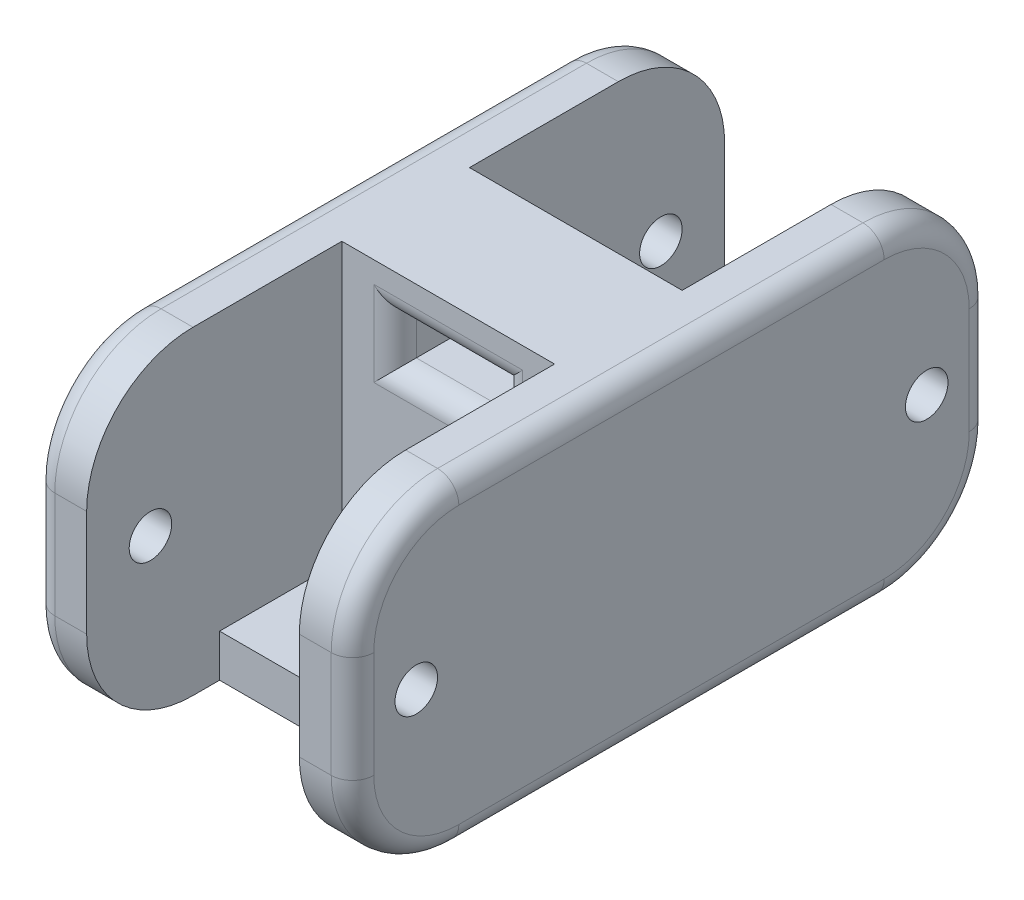
SolidWorks part; units mm, degrees
ref_plane "Front Plane" through (0, 0, 0) normal (0, 0, 1) x (1, 0, 0)
ref_plane "Top Plane" through (0, 0, 0) normal (0, 1, 0) x (1, 0, 0)
ref_plane "Right Plane" through (0, 0, 0) normal (1, 0, 0) x (0, 0, -1)
sketch "Bottom Section Base Sketch" plane through (0, 0, 0) normal (0, 0, 1) x (1, 0, 0)
  line L1 (-7.5, 7.5) -> (7.5, 7.5)
  line L2 (-7.5, 7.5) -> (-7.5, -7.5)
  line L3 (-7.5, -7.5) -> (7.5, -7.5)
  line L4 (7.5, 7.5) -> (7.5, -7.5)
  line L5 (-7.5, 7.5) -> (7.5, -7.5) construction
  line L6 (-7.5, -7.5) -> (7.5, 7.5) construction
  point P0 (0, 0)
  dimension "D1" = 15
  dimension "D2" = 15
extrude "Bottom Section Extrude" add sketch "Bottom Section Base Sketch" along normal blind 30
sketch "Hinge Cutout Sketch" plane through (0, 0, 0) normal (0, 0, 1) x (1, 0, 0)
  line L1 (5, 7.5) -> (-5, 7.5)
  line L2 (5, 7.5) -> (5, -7.5)
  line L3 (5, -7.5) -> (-5, -7.5)
  line L4 (-5, 7.5) -> (-5, -7.5)
  line L5 (7.5, -7.5) -> (7.5, 7.5) construction
  line L6 (0, 0) -> (0, 10.7526) construction
  line L7 (7.5, 7.5) -> (-7.5, 7.5) construction
  line L8 (0, 0) -> (-12.6441, 0) construction
  dimension "D1" = 2.5
extrude "Hinge Cutout Extruded Cut" cut sketch "Hinge Cutout Sketch" along normal blind 12
sketch "Hinge Hole Sketch" plane through (7.5, 0, 0) normal (1, 0, 0) x (0, 0, -1)
  line L0 (0, 0) -> (-29.5332, 0) construction
  line L1 (0, -7.5) -> (0, 7.5) construction
  circle A0 centre (-3, 0) radius 1
  dimension "D1" = 2
  dimension "D2" = 3
extrude "Hinge Hole Extruded Cut" cut sketch "Hinge Hole Sketch" against normal through all
ref_plane "Part Midplane Relative to Front Plane" through (0, 0, 15) normal (0, 0, 1) x (1, 0, 0)
mirror "Hinge and Hole Cutout Mirror" about plane through (0, 0, 15) normal (0, 0, 1) of "Hinge Hole Extruded Cut", "Hinge Cutout Extruded Cut"
fillet "Hinger Corner Fillets" radius 5 8 edges at (6.25, 7.5, 30) (6.25, -7.5, 30) (-6.25, -7.5, 30) (-6.25, 7.5, 30) (-6.25, 7.5, 0) (-6.25, -7.5, 0) (6.25, -7.5, 0) (6.25, 7.5, 0)
fillet "Style Fillets" radius 1 16 edges at (7.5, 6.0355, 28.5355) (7.5, 0, 30) (7.5, -6.0355, 28.5355) (7.5, -7.5, 15) (7.5, -6.0355, 1.4645) (7.5, 0, 0) (7.5, 6.0355, 1.4645) (7.5, 7.5, 15) (-7.5, 6.0355, 28.5355) (-7.5, 0, 30) (-7.5, -6.0355, 28.5355) (-7.5, -7.5, 15) (-7.5, -6.0355, 1.4645) (-7.5, 0, 0) (-7.5, 6.0355, 1.4645) (-7.5, 7.5, 15)
sketch "Routing Holes Sketch" plane through (0, 0, 0) normal (0, 0, 1) x (1, 0, 0)
  line L0 (0, 0) -> (9.2623, 0) construction
  line L1 (0, 0) -> (0, 9.2302) construction
  line L2 (5, 7.5) -> (-5, 7.5) construction
  line L3 (-2.5, 5.5) -> (2.5, 5.5)
  line L4 (-2.5, 5.5) -> (-2.5, 3.5)
  line L5 (-2.5, 3.5) -> (2.5, 3.5)
  line L6 (2.5, 5.5) -> (2.5, 3.5)
  line L7 (2.5, -5.5) -> (2.5, -3.5)
  line L8 (-2.5, -3.5) -> (2.5, -3.5)
  line L9 (-2.5, -5.5) -> (-2.5, -3.5)
  line L10 (-2.5, -5.5) -> (2.5, -5.5)
  dimension "D1" = 2
  dimension "D2" = 2
  dimension "D3" = 5
extrude "Routing Holes Extruded Cut" cut sketch "Routing Holes Sketch" along normal through all
sketch "Backing Sketch" plane through (0, 0, 18) normal (0, 0, 1) x (1, 0, 0)
  line L0 (5, -7.5) -> (5, 7.5) construction
  line L1 (-5, -7.5) -> (5, -7.5)
  line L2 (-5, -7.5) -> (-5, -5.5)
  line L3 (-5, -5.5) -> (5, -5.5)
  line L4 (5, -7.5) -> (5, -5.5)
  line L5 (2.5, -5.5) -> (-2.5, -5.5) construction
extrude "Backing Extrude" add sketch "Backing Sketch" along normal blind 5.75
fillet "Routing Fillets" radius 1 15 edges at (2.5, 4.5, 18) (0, 5.5, 18) (-2.5, 4.5, 18) (0, 3.5, 18) (-2.5, 4.5, 12) (0, 5.5, 12) (2.5, 4.5, 12) (0, 3.5, 12) (2.5, -4.5, 18) (0, -3.5, 18) (-2.5, -4.5, 18) (2.5, -4.5, 12) (0, -3.5, 12) (-2.5, -4.5, 12) (0, -5.5, 12)
